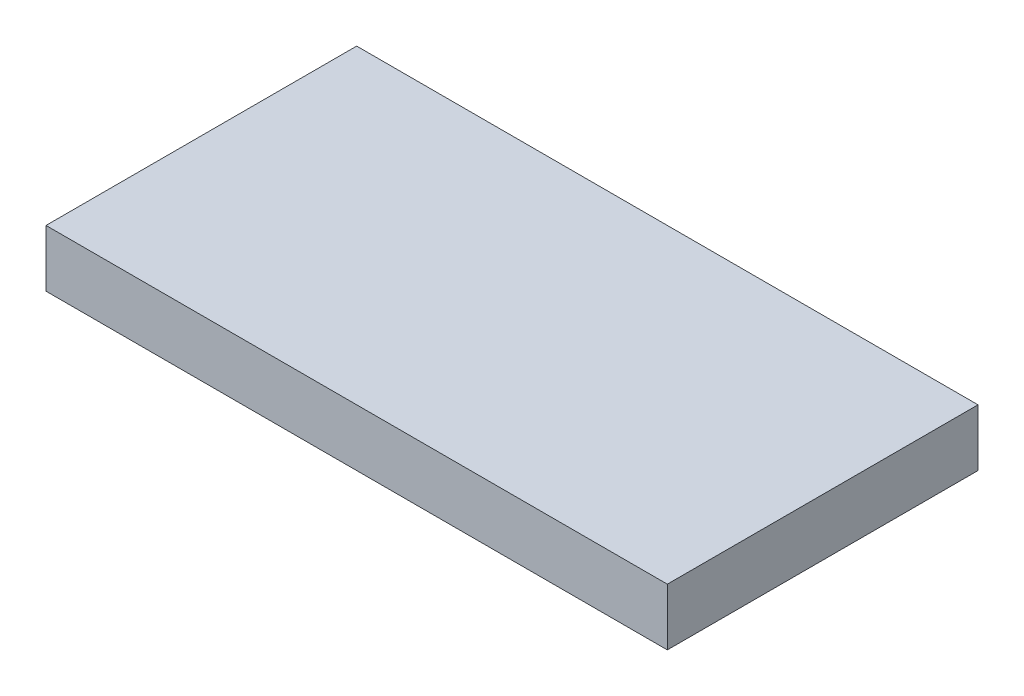
SolidWorks part; units mm, degrees
ref_plane "前视基准面" through (0, 0, 0) normal (0, 0, 1) x (1, 0, 0)
ref_plane "上视基准面" through (0, 0, 0) normal (0, 1, 0) x (1, 0, 0)
ref_plane "右视基准面" through (0, 0, 0) normal (1, 0, 0) x (0, 0, -1)
sketch "草图1" plane through (0, 0, 0) normal (0, 1, 0) x (1, 0, 0)
  line L1 (0, 300) -> (600, 300)
  line L2 (0, 300) -> (0, 0)
  line L3 (0, 0) -> (600, 0)
  line L4 (600, 300) -> (600, 0)
  dimension "D1" = 600
  dimension "D2" = 300
extrude "凸台-拉伸1" add sketch "草图1" along normal blind 55
